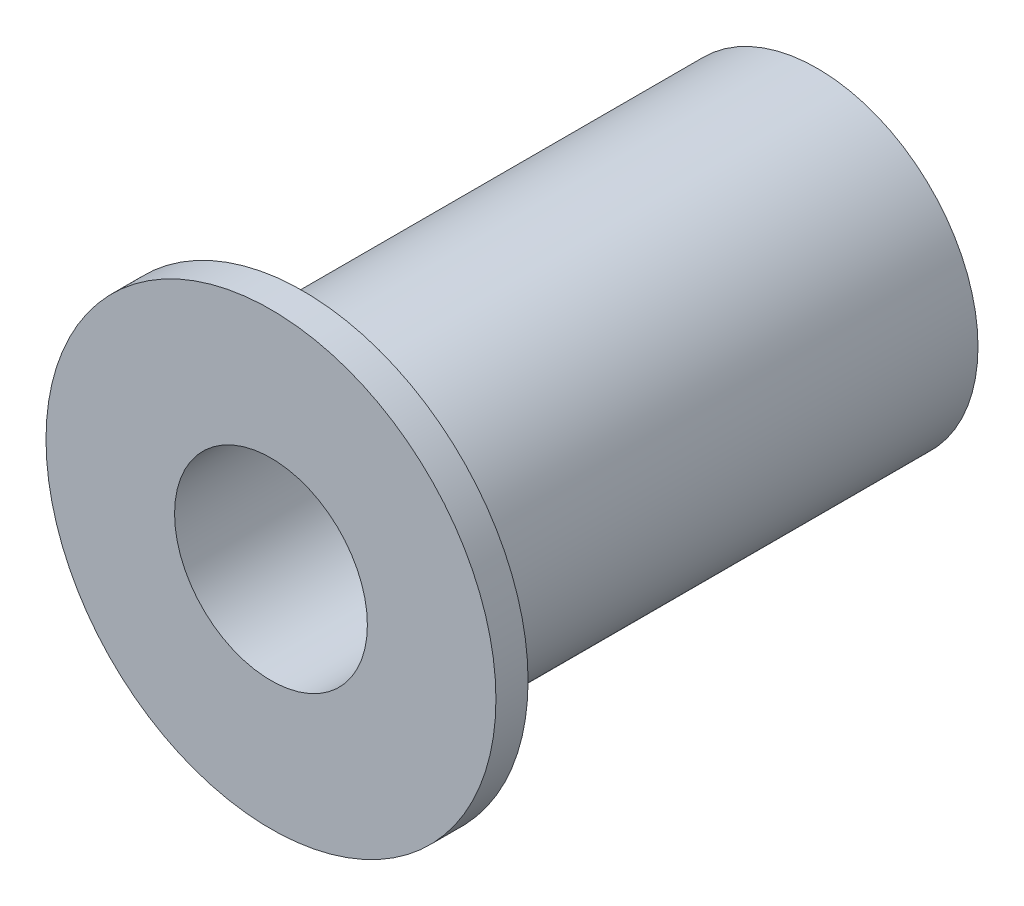
SolidWorks part; units mm, degrees
ref_plane "Front Plane" through (0, 0, 0) normal (0, 0, 1) x (1, 0, 0)
ref_plane "Top Plane" through (0, 0, 0) normal (0, 1, 0) x (1, 0, 0)
ref_plane "Right Plane" through (0, 0, 0) normal (1, 0, 0) x (0, 0, -1)
sketch "Sketch1" plane through (0, 0, 0) normal (0, 0, 1) x (1, 0, 0)
  circle A0 centre (0, 0) radius 7.9375
  circle A1 centre (0, 0) radius 4.7625
  dimension "D1" = 15.875
  dimension "D2" = 9.525
extrude "Boss-Extrude1" add sketch "Sketch1" along normal mid plane 25.4
sketch "Sketch2" plane through (0, 0, 12.7) normal (0, 0, 1) x (1, 0, 0)
  circle A1 centre (0, 0) radius 11.1125
  circle A2 centre (0, 0) radius 4.7625
  circle A3 centre (0, 0) radius 4.7625
  dimension "D2" = 22.225
  dimension "D1" = 0
extrude "Boss-Extrude2" add sketch "Sketch2" along normal blind 1.5875
